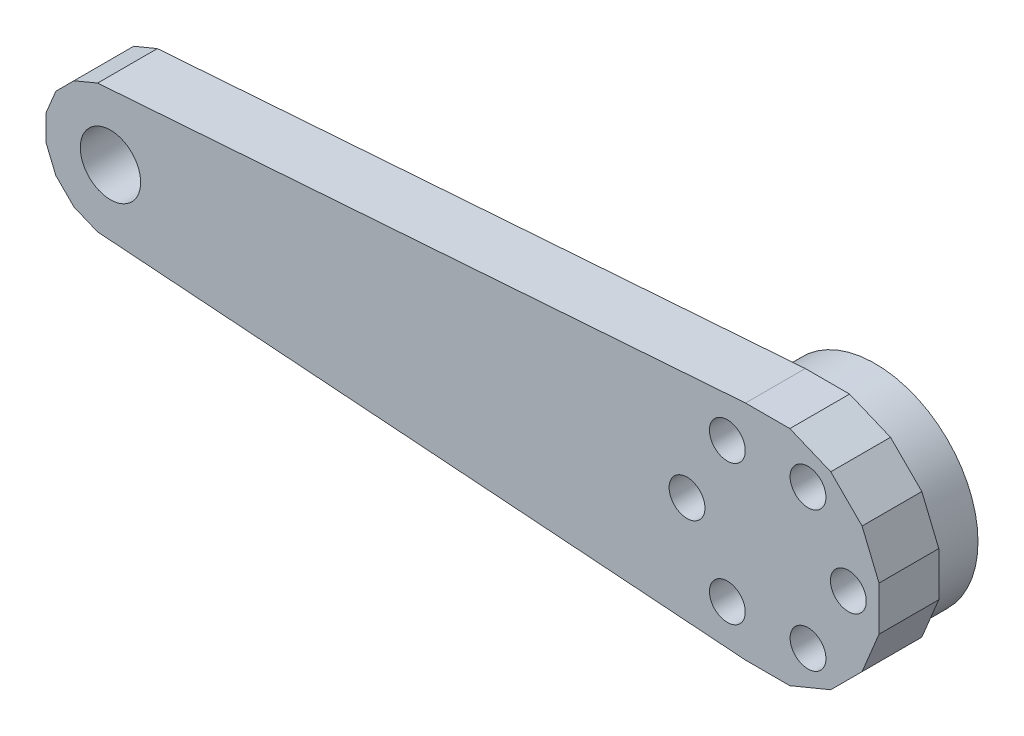
SolidWorks part; units mm, degrees
ref_plane "前视基准面" through (0, 0, 0) normal (0, 0, 1) x (1, 0, 0)
ref_plane "上视基准面" through (0, 0, 0) normal (0, 1, 0) x (1, 0, 0)
ref_plane "右视基准面" through (0, 0, 0) normal (1, 0, 0) x (0, 0, -1)
other "Configuration Table"
sketch "Profile_1" plane through (0, 0, 0) normal (0, 0, 1) x (1, 0, 0)
  line L0 (-116.1113, 9.1462) -> (-119.1462, 6.1113)
  line L1 (-119.1462, 6.1113) -> (-120.7886, 2.146)
  line L2 (-120.7886, 2.146) -> (-120.7886, -2.146)
  line L3 (-120.7886, -2.146) -> (-119.1462, -6.1113)
  line L4 (-119.1462, -6.1113) -> (-116.1113, -9.1462)
  line L5 (-116.1113, -9.1462) -> (-112.146, -10.7886)
  line L6 (-112.146, -10.7886) -> (-3.7067, -18.6349)
  line L7 (-3.7067, -18.6349) -> (3.7067, -18.6349)
  line L8 (3.7067, -18.6349) -> (10.5558, -15.7979)
  line L9 (10.5558, -15.7979) -> (15.7979, -10.5558)
  line L10 (15.7979, -10.5558) -> (18.6349, -3.7067)
  line L11 (18.6349, -3.7067) -> (18.6349, 3.7067)
  line L12 (18.6349, 3.7067) -> (15.7979, 10.5558)
  line L13 (15.7979, 10.5558) -> (10.5558, 15.7979)
  line L14 (10.5558, 15.7979) -> (3.7067, 18.6349)
  line L15 (3.7067, 18.6349) -> (-3.7067, 18.6349)
  line L16 (-3.7067, 18.6349) -> (-112.146, 10.7886)
  line L17 (-112.146, 10.7886) -> (-116.1113, 9.1462)
  circle A0 centre (-110, 0) radius 5.05
  circle A1 centre (-13.5, 0) radius 1.65
  circle A2 centre (-6.75, 11.6913) radius 1.65
  circle A3 centre (6.75, 11.6913) radius 1.65
  circle A4 centre (13.5, 0) radius 1.65
  circle A5 centre (6.75, -11.6913) radius 1.65
  circle A6 centre (-6.75, -11.6913) radius 1.65
extrude "Arm_web" add sketch "Profile_1" along normal blind 10 from offset 8
sketch "Profile_2" plane through (0, 0, 0) normal (0, 0, 1) x (1, 0, 0)
  circle A0 centre (0, 0) radius 17.2
  circle A1 centre (0, 0) radius 5
  circle A2 centre (-13.5, 0) radius 1.65
  circle A3 centre (-6.75, 11.6913) radius 1.65
  circle A4 centre (6.75, 11.6913) radius 1.65
  circle A5 centre (13.5, 0) radius 1.65
  circle A6 centre (6.75, -11.6913) radius 1.65
  circle A7 centre (-6.75, -11.6913) radius 1.65
extrude "Rotor_standoff" add sketch "Profile_2" along normal blind 8 from offset 0
sketch "Profile_3" plane through (0, 0, 0) normal (0, 0, 1) x (1, 0, 0)
  circle A0 centre (-13.5, 0) radius 3
  circle A1 centre (-6.75, 11.6913) radius 3
  circle A2 centre (6.75, 11.6913) radius 3
  circle A3 centre (13.5, 0) radius 3
  circle A4 centre (6.75, -11.6913) radius 3
  circle A5 centre (-6.75, -11.6913) radius 3
extrude "Rotor_screw_spotfaces" cut sketch "Profile_3" along normal blind 6.01 from offset 12
